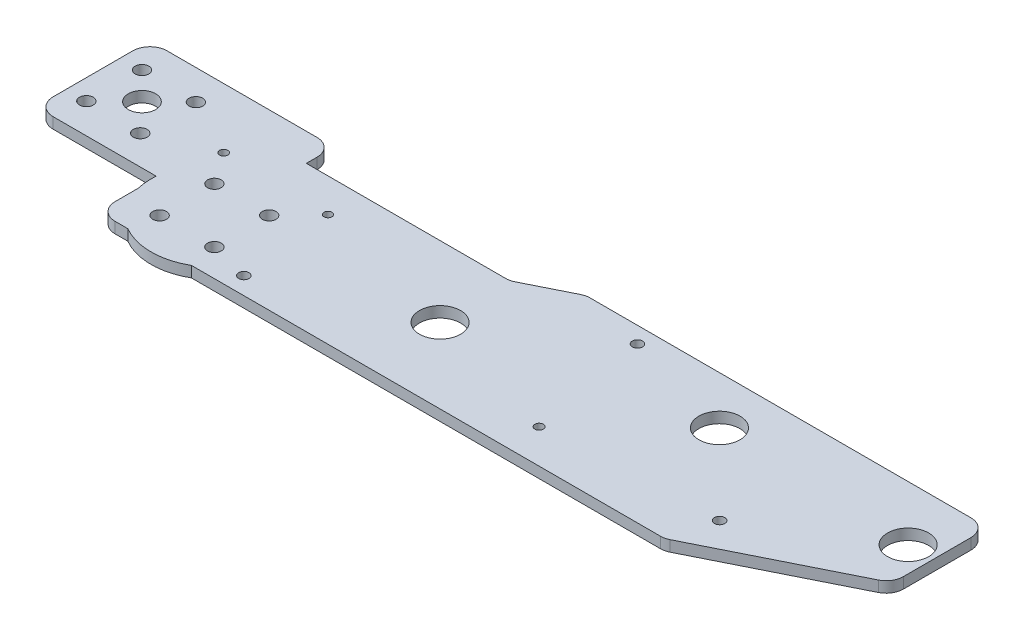
SolidWorks part; units mm, degrees
ref_plane "Front" through (0, 0, 0) normal (0, 0, 1) x (1, 0, 0)
ref_plane "Top" through (0, 0, 0) normal (0, 1, 0) x (1, 0, 0)
ref_plane "Right" through (0, 0, 0) normal (1, 0, 0) x (0, 0, -1)
sketch "Sketch1" plane through (0, 0, 0) normal (0, 1, 0) x (1, 0, 0)
  line L1 (0, 0) -> (210, 0)
  line L2 (0, 0) -> (0, -50)
  line L3 (0, -50) -> (210, -50)
  line L4 (210, 0) -> (210, -50)
  circle A7 centre (3.4895, -16.7877) radius 1.2117
  circle A8 centre (34.3726, -17.194) radius 1.1656
  circle A9 centre (37.5207, -44.9212) radius 1.5
  circle A10 centre (118.879, -40.0177) radius 1.25
  circle A11 centre (112.3021, -4.7393) radius 1.5
  circle A12 centre (168.9752, -37.4032) radius 1.5173
  dimension "D1" = 210
  dimension "D2" = 50
extrude "Boss-Extrude1" add sketch "Sketch1" along normal blind 3.175
sketch "Sketch2" plane through (0, 3.175, 0) normal (0, 1, 0) x (1, 0, 0)
  line L0 (210, 0) -> (0, 0) construction
  line L1 (0, 0) -> (0, -50) construction
  circle A0 centre (10, -26) radius 2
  circle A1 centre (10, -42) radius 2
  circle A2 centre (26, -26) radius 2
  circle A3 centre (26, -42) radius 2
  dimension "D1" = 16
  dimension "D2" = 16
  dimension "D3" = 16
  dimension "D4" = 26
  dimension "D5" = 10
  dimension "D6" = 10
  dimension "D7" = 26
  dimension "D8" = 16
extrude "Cut-Extrude1" cut sketch "Sketch2" against normal blind 10
sketch "Sketch3" plane through (0, 3.175, 0) normal (0, 1, 0) x (1, 0, 0)
  line L0 (210, 0) -> (0, 0) construction
  line L1 (210, 0) -> (0, 0) construction
  circle A0 centre (78.0103, -28.1) radius 6
  circle A1 centre (145.5313, -14) radius 6
  circle A2 centre (18, -34) radius 0.587
  circle A3 centre (26, -26) radius 2 construction
  circle A4 centre (202.6463, -16) radius 6
  dimension "D1" = 28.1
  dimension "D3" = 16
  dimension "D4" = 14
  dimension "D7" = 125.222
  dimension "D2" = 60.2996
  dimension "D5" = 8
  dimension "D6" = 8
  dimension "D8" = 57.15
extrude "Cut-Extrude2" cut sketch "Sketch3" against normal blind 57.15
sketch "Sketch4" [suppressed] plane through (0, 3.175, 0) normal (0, 1, 0) x (1, 0, 0)
  line L0 (3.4895, -16.7877) -> (18, -34)
  line L1 (3.4895, -20.6627) -> (5.9498, -23.5811)
  line L2 (18, -34) -> (34.3726, -17.194)
  line L3 (34.3726, -17.194) -> (75.8499, -28.1)
  line L4 (75.8499, -28.1) -> (37.5207, -44.9212)
  line L5 (7.3432, -17.194) -> (9.8664, -20.303)
  circle A0 centre (18, -34) radius 15.9299
  circle A1 centre (3.4895, -16.7877) radius 3.8751
  circle A2 centre (34.3726, -17.194) radius 3.7227
  circle A3 centre (37.5207, -44.9212) radius 3.8676
  circle A4 centre (75.8499, -28.1) radius 12.797
  circle A5 centre (112.3021, -4.7393) radius 5.1588
  circle A6 centre (118.879, -40.0177) radius 4.9035
  circle A7 centre (140.772, -16) radius 12.6375
  circle A8 centre (168.9752, -37.4032) radius 4.2066
  circle A9 centre (197.922, -16) radius 12.8
sketch "Sketch5" [suppressed] plane through (0, 3.175, 0) normal (0, 1, 0) x (1, 0, 0)
  line L0 (210, 0) -> (0, 0) construction
  line L2 (-0.6266, -16.7877) -> (37.5207, -16.7877)
  line L3 (-0.6266, -16.7877) -> (-0.6266, -44.9212)
  line L4 (-0.6266, -44.9212) -> (37.5207, -44.9212)
  line L5 (37.5207, -16.7877) -> (37.5207, -44.9212)
  line L6 (75.8499, -15.182) -> (37.5207, -15.182)
  line L7 (75.8499, -15.182) -> (75.8499, -44.9212)
  line L8 (75.8499, -44.9212) -> (37.5207, -44.9212)
  line L9 (37.5207, -15.182) -> (37.5207, -44.9212)
  line L10 (112.3021, -4.7393) -> (75.8499, -4.7393)
  line L11 (112.3021, -4.7393) -> (112.3021, -44.9212)
  line L12 (112.3021, -44.9212) -> (75.8499, -44.9212)
  line L13 (75.8499, -4.7393) -> (75.8499, -44.9212)
  line L14 (112.3021, -4.7393) -> (102.3945, -4.7393)
  line L16 (112.3021, -4.7393) -> (112.3021, 0)
  line L17 (112.3021, 0) -> (102.3945, 0)
  line L18 (102.3945, -4.7393) -> (102.3945, 0)
  line L19 (210, -50) -> (210, 0) construction
  line L20 (112.3021, -4.7393) -> (123.1553, -4.7393)
  line L21 (112.3021, -4.7393) -> (112.3021, 0)
  line L22 (112.3021, 0) -> (123.1553, 0)
  line L23 (123.1553, -4.7393) -> (123.1553, 0)
  line L24 (112.3021, -4.7393) -> (140.772, -4.7393)
  line L25 (112.3021, -4.7393) -> (112.3021, -40.0177)
  line L26 (112.3021, -40.0177) -> (140.772, -40.0177)
  line L27 (140.772, -4.7393) -> (140.772, -40.0177)
  line L28 (140.772, -16) -> (168.9752, -16)
  line L29 (140.772, -16) -> (140.772, -40.0177)
  line L30 (140.772, -40.0177) -> (168.9752, -40.0177)
  line L31 (168.9752, -16) -> (168.9752, -40.0177)
  line L32 (168.9752, -4.7393) -> (210, -4.7393)
  line L33 (168.9752, -4.7393) -> (168.9752, -40.0177)
  line L34 (168.9752, -40.0177) -> (210, -40.0177)
  line L35 (210, -4.7393) -> (210, -40.0177)
  line L36 (0, -50) -> (210, -50) construction
  line L37 (160.7629, -40.0177) -> (177.2091, -40.0177)
  line L38 (160.7629, -40.0177) -> (160.7629, -44.9212)
  line L39 (160.7629, -44.9212) -> (177.2091, -44.9212)
  line L40 (177.2091, -40.0177) -> (177.2091, -44.9212)
  line L41 (112.3021, -40.0177) -> (126.3591, -40.0177)
  line L42 (112.3021, -40.0177) -> (112.3021, -47.7828)
  line L43 (112.3021, -47.7828) -> (126.3591, -47.7828)
  line L44 (126.3591, -40.0177) -> (126.3591, -47.7828)
  line L45 (30.5963, -44.9212) -> (44.6115, -44.9212)
  line L46 (30.5963, -44.9212) -> (30.5963, -50)
  line L47 (30.5963, -50) -> (44.6115, -50)
  line L48 (44.6115, -44.9212) -> (44.6115, -50)
  line L50 (-0.6266, -44.9212) -> (30.5963, -44.9212)
  line L51 (-0.6266, -44.9212) -> (-0.6266, -50)
  line L52 (-0.6266, -50) -> (30.5963, -50)
  line L53 (30.5963, -44.9212) -> (30.5963, -50)
  circle A0 centre (3.4895, -16.7877) radius 4.1161
  circle A1 centre (34.3726, -17.194) radius 3.8132
  circle A2 centre (75.8499, -28.1) radius 12.918
  circle A3 centre (112.3021, -4.7393) radius 5.2663
  circle A4 centre (140.772, -16) radius 13.0245
  circle A5 centre (197.922, -16) radius 12.3805
  circle A6 centre (168.9752, -37.4032) radius 4.7643
  circle A7 centre (118.879, -40.0177) radius 5.279
  circle A8 centre (37.5207, -44.9212) radius 4.2049
  line M12 (0, 0) -> (0, -50)
  line M13 (0, -50) -> (210, -50)
  line M14 (210, -50) -> (210, 0)
  line M15 (210, 0) -> (0, 0)
extrude "Cut-Extrude5" [suppressed] cut sketch "Sketch5" against normal blind 11.52 contours A5 L32 L23 L24 A4 L28 L33 M14 M15 | A1 L6 L13 L10 L18 A0 L2 M15 M12 | L8 L48 L34 L40 L39 L38 L30 L26 L44 L43 L42 L12 M13 M14
fillet "Fillet1" [suppressed] radius 5
sketch "Sketch10" plane through (0, 3.175, 0) normal (0, 1, 0) x (1, 0, 0)
  line L0 (210, -27.8594) -> (165.5029, -50)
  line L1 (210, -50) -> (210, 0) construction
  line L2 (0, -50) -> (210, -50) construction
  line L3 (165.5029, -50) -> (210, -50)
  line L4 (210, -50) -> (210, -27.8594)
  line L5 (92.5326, 0) -> (77.6548, -7.4028)
  line L6 (210, 0) -> (0, 0) construction
  line L7 (77.6548, -7.4028) -> (0, -7.4028)
  line L8 (0, 0) -> (0, -50) construction
  line L9 (0, -7.4028) -> (0, 0)
  line L10 (0, 0) -> (92.5326, 0)
extrude "Cut-Extrude7" cut sketch "Sketch10" against normal blind 10
fillet "Fillet3" radius 5 5 edges at (77.6548, 1.5875, 7.4028) (92.5326, 1.5875, 0) (210, 1.5875, 0) (210, 1.5875, 27.8594) (165.5029, 1.5875, 50)
sketch "Sketch11" plane through (0, 3.175, 0) normal (0, 1, 0) x (1, 0, 0)
  circle A0 centre (18, -34) radius 18.5
  circle A1 centre (10, -26) radius 2
  circle A2 centre (10, -42) radius 2
  circle A3 centre (26, -26) radius 2
  circle A4 centre (26, -42) radius 2
extrude "Boss-Extrude4" add sketch "Sketch11" against normal blind 3.175
sketch "Sketch16" plane through (0, 0, 7.4028) normal (0, 0, -1) x (-1, 0, 0)
  line L0 (0, 3.175) -> (-76.4796, 3.175) construction
  line L1 (0, 0) -> (-18.2576, 0)
  line L2 (0, 0) -> (0, 3.175)
  line L3 (0, 3.175) -> (-18.2576, 3.175)
  line L4 (-18.2576, 0) -> (-18.2576, 3.175)
extrude "Boss-Extrude7" add sketch "Sketch16" along normal blind 8.128
sketch "Sketch17" plane through (0, 0, 0) normal (-1, 0, 0) x (0, 0, 1)
  line L0 (-0.7252, 3.175) -> (29.728, 3.175) construction
  line L1 (-0.7252, 0) -> (32.5748, 0)
  line L2 (-0.7252, 0) -> (-0.7252, 3.175)
  line L3 (-0.7252, 3.175) -> (32.5748, 3.175)
  line L4 (32.5748, 0) -> (32.5748, 3.175)
  dimension "D1" = 33.3
extrude "Boss-Extrude8" add sketch "Sketch17" along normal blind 35.56
sketch "Sketch18" plane through (0, 3.175, 0) normal (0, 1, 0) x (1, 0, 0)
  line L0 (-35.56, 0.7252) -> (18.2576, 0.7252) construction
  circle A0 centre (-21.4859, -15.9248) radius 11.315
  circle A1 centre (-29.612, -23.7985) radius 2
  circle A2 centre (-29.3597, -7.7987) radius 2
  circle A3 centre (-13.3598, -8.0511) radius 2
  circle A4 centre (-13.6122, -24.0509) radius 2
  circle A5 centre (-21.4859, -15.9248) radius 4
  point P15 (-21.4859, -15.9248)
  dimension "D1" = 22.63
  dimension "D3" = 4
  dimension "D2" = 16.65
extrude "Cut-Extrude8" cut sketch "Sketch18" against normal blind 9 contours A2 | A1 | A4 | A3
sketch "Sketch19" plane through (0, 3.175, 0) normal (0, 1, 0) x (1, 0, 0)
  circle A0 centre (-21.3597, -15.7987) radius 4
  circle A1 centre (-29.3597, -7.7987) radius 2 construction
  dimension "D1" = 8
  dimension "D2" = 8
extrude "Cut-Extrude9" cut sketch "Sketch19" against normal blind 40
fillet "Fillet4" radius 5 4 edges at (0, 1.5875, 50) (18.2576, 1.5875, -0.7252) (-35.56, 1.5875, -0.7252) (-35.56, 1.5875, 32.5748)
